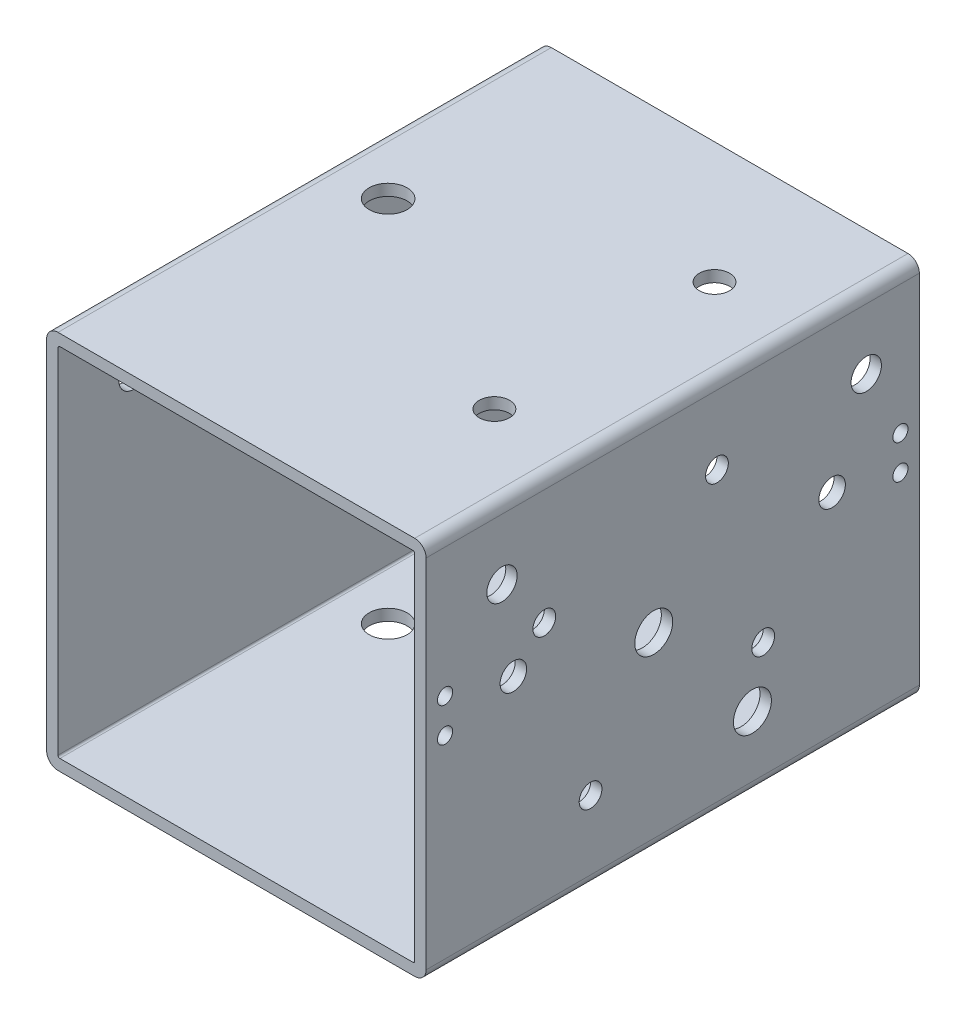
SolidWorks part; units mm, degrees
ref_plane "Front Plane" through (0, 0, 0) normal (0, 0, 1) x (1, 0, 0)
ref_plane "Top Plane" through (0, 0, 0) normal (0, 1, 0) x (1, 0, 0)
ref_plane "Right Plane" through (0, 0, 0) normal (1, 0, 0) x (0, 0, -1)
sketch "Sketch1" plane through (0, 0, 0) normal (0, 0, 1) x (1, 0, 0)
  line L1 (-50, 50) -> (50, 50)
  line L2 (-50, 50) -> (-50, -50)
  line L3 (-50, -50) -> (50, -50)
  line L4 (50, 50) -> (50, -50)
  line L5 (-50, 50) -> (50, -50) construction
  line L6 (-50, -50) -> (50, 50) construction
  point P0 (0, 0)
  dimension "D1" = 100
  dimension "D2" = 100
extrude "Extrude-Thin1" add sketch "Sketch1" along normal blind 130 thin
fillet "Fillet1" radius 0.5 4 edges at (-47, -47, 65) (-47, 47, 65) (47, 47, 65) (47, -47, 65)
fillet "Fillet2" radius 3 4 edges at (50, -50, 65) (-50, -50, 65) (50, 50, 65) (-50, 50, 65)
sketch "Holes - top" plane through (0, 0, 0) normal (0, 1, 0) x (1, 0, 0)
  line L0 (-3, 0) -> (-3, -130) construction
  line L1 (47, -130) -> (-47, -130) construction
  line L2 (-23, 0) -> (-23, -130) construction
  line L3 (47, 0) -> (-47, 0) construction
  line L4 (17, 0) -> (17, -130) construction
  circle A0 centre (-34, -56) radius 11 construction
  circle A1 centre (28, -90) radius 11 construction
  circle A2 centre (28, -32) radius 11 construction
  dimension "D4" = 22
  dimension "D1" = 40
  dimension "D2" = 40
  dimension "D3" = 32
  dimension "D5" = 56
  dimension "D6" = 3
hole_wizard "Ø8.0 (8) Diameter Hole2" positions "Sketch6" profile "Sketch5" hole size "Ø8.0" standard "ANSI Metric" end condition through all
sketch "Sketch6" plane through (0, 50, 0) normal (0, 1, 0) x (1, 0, 0)
  point P0 (28, -32)
  point P6 (28, -90)
sketch "Sketch5" plane through (28, 50, 32) normal (1, 0, 0) x (0, 0, 1)
  line L0 (0, 0) -> (0, 100)
  line L1 (0, 100) -> (4, 100)
  line L2 (4, 100) -> (4, 0)
  line L5 (4, 0) -> (0, 0)
  line L11 (0, -6.35) -> (0, 107.95) construction
  dimension "Thru Hole Dia." = 8
  dimension "Thru Hole Depth" = 100
sketch "Holes - side" plane through (0, 0, 0) normal (1, 0, 0) x (0, 0, -1)
  line L0 (0, 0) -> (-130, 0) construction
  line L1 (-130, -47) -> (-130, 47) construction
  line L2 (-130, 20) -> (0, 20) construction
  line L3 (0, -47) -> (0, 47) construction
  line L4 (-130, -20) -> (0, -20) construction
  circle A0 centre (-110, 31) radius 11 construction
  circle A1 centre (-14, 31) radius 11 construction
  circle A2 centre (-44, -31) radius 11 construction
  dimension "D1" = 40
  dimension "D2" = 22
  dimension "D3" = 20
  dimension "D4" = 14
  dimension "D5" = 44
hole_wizard "Ø8.0 (8) Diameter Hole3" positions "Sketch9" profile "Sketch8" hole size "Ø8.0" standard "ANSI Metric" end condition through all
sketch "Sketch9" plane through (50, 0, 0) normal (1, 0, 0) x (0, 0, -1)
  point P0 (-14, 31)
  point P3 (-110, 31)
sketch "Sketch8" plane through (50, 31, 14) normal (0, 1, 0) x (0, 0, -1)
  line L0 (0, 0) -> (0, 100)
  line L1 (0, 100) -> (4, 100)
  line L2 (4, 100) -> (4, 0)
  line L5 (4, 0) -> (0, 0)
  line L11 (0, -6.35) -> (0, 107.95) construction
  dimension "Thru Hole Dia." = 8
  dimension "Thru Hole Depth" = 100
hole_wizard "Ø10.0 (10) Diameter Hole1" positions "Sketch12" profile "Sketch11" hole size "Ø10.0" standard "ANSI Metric" end condition through all
sketch "Sketch12" plane through (0, 50, 0) normal (0, 1, 0) x (1, 0, 0)
  point P0 (-34, -56)
sketch "Sketch11" plane through (-34, 50, 56) normal (1, 0, 0) x (0, 0, 1)
  line L0 (0, 0) -> (0, 100)
  line L1 (0, 100) -> (5, 100)
  line L2 (5, 100) -> (5, 0)
  line L5 (5, 0) -> (0, 0)
  line L11 (0, -6.35) -> (0, 107.95) construction
  dimension "Thru Hole Dia." = 10
  dimension "Thru Hole Depth" = 100
hole_wizard "Ø10.0 (10) Diameter Hole2" positions "Sketch14" profile "Sketch13" hole size "Ø10.0" standard "ANSI Metric" end condition through all
sketch "Sketch14" plane through (50, 0, 0) normal (1, 0, 0) x (0, 0, -1)
  point P0 (-44, -31)
sketch "Sketch13" plane through (50, -31, 44) normal (0, 1, 0) x (0, 0, -1)
  line L0 (0, 0) -> (0, 100)
  line L1 (0, 100) -> (5, 100)
  line L2 (5, 100) -> (5, 0)
  line L5 (5, 0) -> (0, 0)
  line L11 (0, -6.35) -> (0, 107.95) construction
  dimension "Thru Hole Dia." = 10
  dimension "Thru Hole Depth" = 100
hole_wizard "M8x1.25 Tapped Hole1" positions "Sketch18" profile "Sketch17" tap size "M8x1.25" standard "ANSI Metric"
sketch "Sketch18" plane through (-50, 0, 0) normal (-1, 0, 0) x (0, 0, 1)
  line L0 (56, 35) -> (56, -15) construction
  point P0 (56, -15)
  point P2 (56, 35)
  dimension "D1" = 56
  dimension "D2" = 35
  dimension "D3" = 15
sketch "Sketch17" plane through (-50, -15, 56) normal (0, 1, 0) x (0, 0, 1)
  line L0 (0, 0) -> (0, 3)
  line L1 (0, 3) -> (3.4, 3)
  line L2 (3.4, 3) -> (3.4, 0)
  line L5 (3.4, 0) -> (0, 0)
  line L11 (0, -6.35) -> (0, 107.95) construction
  dimension "Thru Tap Drill Dia." = 6.8
  dimension "Thru Tap Drill Depth" = 3
cosmetic thread "Hole Thread1" parameters "D2"=8
cosmetic thread "Hole Thread2" parameters "D2"=8
hole_wizard "M8x1.25 Tapped Hole2" positions "Sketch21" profile "Sketch20" tap size "M8x1.25" standard "ANSI Metric"
sketch "Sketch21" plane through (0, -50, 0) normal (0, -1, 0) x (-1, 0, 0)
  line L0 (20, -44) -> (-35, -44) construction
  point P0 (20, -44)
  point P2 (-35, -44)
  dimension "D1" = 44
  dimension "D2" = 35
  dimension "D3" = 20
sketch "Sketch20" plane through (-20, -50, 44) normal (1, 0, 0) x (0, 0, -1)
  line L0 (0, 0) -> (0, 3)
  line L1 (0, 3) -> (3.4, 3)
  line L2 (3.4, 3) -> (3.4, 0)
  line L5 (3.4, 0) -> (0, 0)
  line L11 (0, -6.35) -> (0, 107.95) construction
  dimension "Thru Tap Drill Dia." = 6.8
  dimension "Thru Tap Drill Depth" = 3
cosmetic thread "Hole Thread3" parameters "D2"=8
cosmetic thread "Hole Thread4" parameters "D2"=8
sketch "Holes - Nema 23 motor" plane through (0, 0, 0) normal (1, 0, 0) x (0, 0, -1)
  line L0 (-98.8427, 16.6524) -> (-53.3476, 28.8427) construction
  line L1 (-98.8427, 16.6524) -> (-86.6524, -28.8427) construction
  line L2 (-53.3476, 28.8427) -> (-41.1573, -16.6524) construction
  line L3 (-86.6524, -28.8427) -> (-41.1573, -16.6524) construction
  line L4 (-98.8427, 16.6524) -> (-41.1573, -16.6524) construction
  line L5 (-53.3476, 28.8427) -> (-86.6524, -28.8427) construction
  line L6 (0, 0) -> (-130, 0) construction
  point P1 (-70, 0)
  dimension "D1" = 70
  dimension "D2" = 47.1
  dimension "D3" = 47.1
  dimension "D4" = 15
hole_wizard "Ø10.0 (10) Diameter Hole3" positions "Sketch24" profile "Sketch23" hole size "Ø10.0" standard "ANSI Metric"
sketch "Sketch24" plane through (50, 0, 0) normal (1, 0, 0) x (0, 0, -1)
  point P0 (-70, 0)
sketch "Sketch23" plane through (50, 0, 70) normal (0, 1, 0) x (0, 0, -1)
  line L0 (0, 0) -> (0, 3)
  line L1 (0, 3) -> (5, 3)
  line L2 (5, 3) -> (5, 0)
  line L5 (5, 0) -> (0, 0)
  line L11 (0, -6.35) -> (0, 107.95) construction
  dimension "Thru Hole Dia." = 10
  dimension "Thru Hole Depth" = 3
hole_wizard "Ø6.0 (6) Diameter Hole1" positions "Sketch26" profile "Sketch25" hole size "Ø6.0" standard "ANSI Metric"
sketch "Sketch26" plane through (50, 0, 0) normal (1, 0, 0) x (0, 0, -1)
  point P0 (-41.1573, -16.6524)
  point P3 (-53.3476, 28.8427)
  point P6 (-98.8427, 16.6524)
  point P9 (-86.6524, -28.8427)
sketch "Sketch25" plane through (50, -16.6524, 41.1573) normal (0, 1, 0) x (0, 0, -1)
  line L0 (0, 0) -> (0, 3)
  line L1 (0, 3) -> (3, 3)
  line L2 (3, 3) -> (3, 0)
  line L5 (3, 0) -> (0, 0)
  line L11 (0, -6.35) -> (0, 107.95) construction
  dimension "Thru Hole Dia." = 6
  dimension "Thru Hole Depth" = 3
sketch "Sketch27" plane through (50, 0, 0) normal (1, 0, 0) x (0, 0, -1)
  line L1 (0, -47) -> (0, 47) construction
  line L2 (-130, 50) -> (0, 50) construction
  line L3 (-65, 66.9997) -> (-65, -40.3101) construction
  line L4 (-130, -47) -> (-130, 47) construction
  circle A0 centre (-5, 13) radius 2
  circle A1 centre (-5, 4) radius 2
  circle A2 centre (-23, 8.5) radius 3.5
  circle A3 centre (-107, 8.5) radius 3.5
  circle A4 centre (-125, 4) radius 2
  circle A5 centre (-125, 13) radius 2
  dimension "D1" = 4
  dimension "D2" = 9
  dimension "D3" = 5
  dimension "D4" = 46
  dimension "D7" = 18
  dimension "D8" = 4.5
  dimension "D9" = 7
  dimension "D5" = 0
  dimension "D6" = 65
extrude "Cut-Extrude1" cut sketch "Sketch27" against normal up to next
equation "\"a\"= \"Trolley Profile@Plasma Beta.Assembly\""
equation "\"b\"= \"Trolley Profile Thickness@Plasma Beta.Assembly\""
equation "\"L\"= 130"
equation "\"D2@Sketch1\"=\"a\""
equation "\"D1@Sketch1\"=\"a\""
equation "\"D1@Extrude-Thin1\"=\"L\""
equation "\"D5@Extrude-Thin1\"=\"b\""
equation "\"D1@Fillet2\"=\"b\""
equation "\"d-bearing\"= 22'diameter of bearing"
equation "\"a-small\"= \"Beam Profile@Plasma Beta.Assembly\"'profile of smaller beam"
equation "\"D4@Holes - top\"=\"d-bearing\""
equation "\"D2@Holes - side\"=\"d-bearing\""
equation "\"D1@Holes - top\"=\"a-small\""
equation "\"D1@Holes - side\"=\"a-small\""
